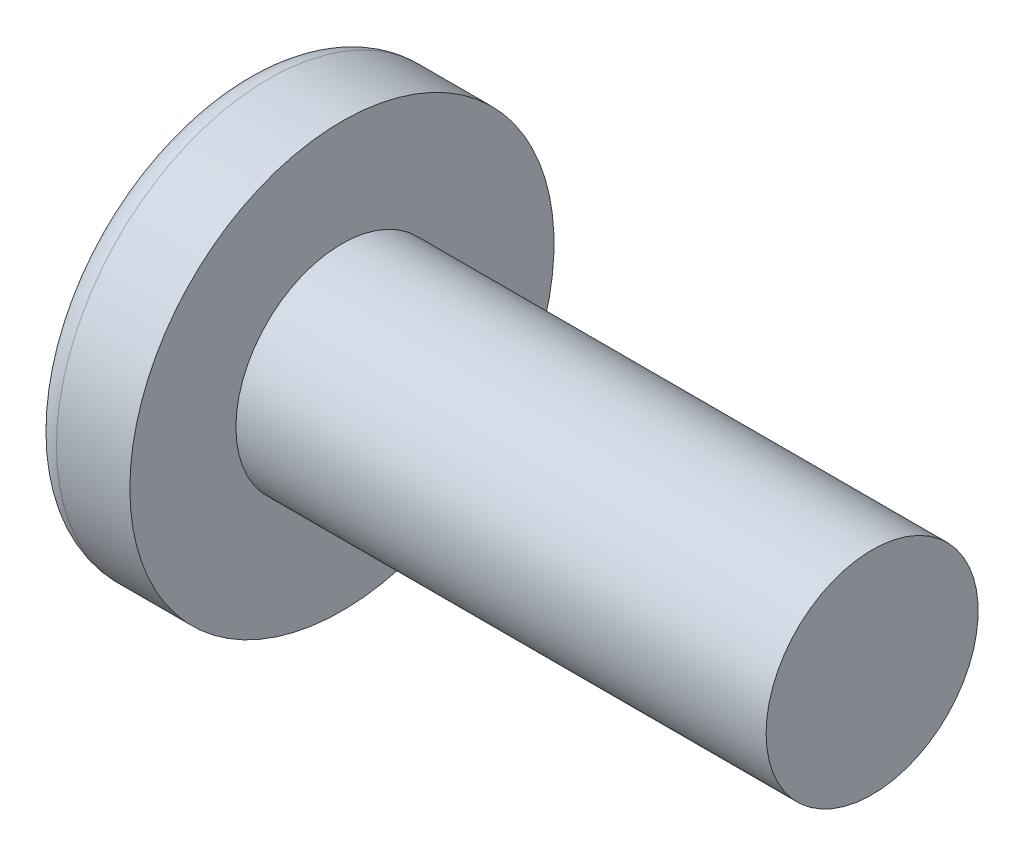
SolidWorks part; units mm, degrees
ref_plane "Plane1" through (0, 0, 0) normal (0, 0, 1) x (1, 0, 0)
ref_plane "Plane2" through (0, 0, 0) normal (0, 1, 0) x (1, 0, 0)
ref_plane "Plane3" through (0, 0, 0) normal (1, 0, 0) x (0, 0, -1)
sketch "BodySke" plane through (0, 0, 0) normal (0, 0, 1) x (1, 0, 0)
  line L0 (6, 4) -> (6, 8)
  line L1 (7.25, 6.35) -> (7.25, -3.175) construction
  line L2 (-25.4, 0) -> (127, 0) construction
  line L3 (26, 0) -> (0, 0)
  line L4 (6, 4) -> (26, 4)
  line L5 (26, 4) -> (26, 0)
  line L6 (3.2327, 8) -> (6, 8)
  line L7 (6, -4) -> (26, -4) construction
  line L8 (6, 6.35) -> (6, -3.175) construction
  arc A0 (2.4539, 7.6013) -> (0, 0) centre (13, 0) ccw
  arc A2 (2.4539, 7.6013) -> (3.2327, 8) centre (3.2327, 7.04) cw
  dimension "Head_crown_rad" = 13
  dimension "Head_fillet_rad" = 0.96
  dimension "Diameter" = 8
  dimension "Length" = 20
  dimension "Head_ht" = 6
  dimension "Head_dia" = 16
  dimension "Advance" = 1.25
  dimension "Thread_nom" = 20
revolve "Base-Revolve" add sketch "BodySke" angle 360 about L2
cosmetic thread "ThreadCosmetic" [suppressed] parameters "Thread_length"=18.75, "Thread_minor"=6.619
sketch "Sketch3" plane through (0, 0, 0) normal (1, 0, 0) x (0, 0, -1)
  line L0 (0.845, -4.51) -> (-0.845, -4.51)
  line L1 (0.845, -4.51) -> (0.845, 4.51)
  line L2 (-0.845, 4.51) -> (0.845, 4.51)
  line L3 (-0.845, 4.51) -> (-0.845, -4.51)
  dimension "Cross_dia" = 9.02
  dimension "D1" = 4.51
  dimension "Cross_width" = 1.69
  dimension "D2" = 0.845
ref_plane "Plane4" through (4.88, 0, 0) normal (1, 0, 0) x (0, 0, -1)
sketch "Sketch4" plane through (4.88, 0, 0) normal (1, 0, 0) x (0, 0, -1)
  line L0 (0.4225, -0.4225) -> (-0.4225, -0.4225)
  line L1 (0.4225, -0.4225) -> (0.4225, 0.4225)
  line L2 (-0.4225, 0.4225) -> (0.4225, 0.4225)
  line L3 (-0.4225, 0.4225) -> (-0.4225, -0.4225)
  dimension "D2" = 0.845
  dimension "D1" = 0.845
  dimension "D3" = 0.4225
  dimension "D4" = 0.4225
loft "Cut-Loft1" cut profiles "Sketch3", "Sketch4"
pattern_circular "CirPattern1" count 2 every 90 about axis through (0, 0, 0) along (1, 0, 0) of "Cut-Loft1"
sketch "ThdSchSke" plane through (0, 0, 0) normal (0, 0, 1) x (1, 0, 0)
  line L0 (7.25, -3.3095) -> (6.7665, -4)
  line L1 (7.25, -3.3095) -> (7.7335, -4)
  line L2 (7.7335, -4) -> (7.7335, -5)
  line L3 (-3.175, 0) -> (5.1513, 0) construction
  line L5 (7.7335, -5) -> (6.7665, -5)
  line L6 (6.7665, -5) -> (6.7665, -4)
  dimension "Diameter" = 8
  dimension "SideAngle" = 55
  dimension "VeeAngle" = 70
  dimension "Thread_minor" = 6.619
  dimension "Overcut" = 10
  dimension "Start" = 7.25
revolve "ThreadSchematic" [suppressed] cut sketch "ThdSchSke" angle 360 about L3
pattern_linear "ThdSchPat" [suppressed]
equation "\"D1@Sketch3\" = \"Cross_dia@Sketch3\" / 2"
equation "\"D2@Sketch3\" = \"Cross_width@Sketch3\" / 2"
equation "\"D1@Sketch4\" = \"Cross_width@Sketch3\" *.5"
equation "\"D2@Sketch4\" = \"D1@Sketch4\""
equation "\"D3@Sketch4\" = \"D1@Sketch4\" / 2"
equation "\"D4@Sketch4\" = \"D2@Sketch4\" / 2"
equation "\"Thread_length@ThreadCosmetic\" = ((sgn( (\"Length@BodySke\" - \"Advance@BodySke\" ) - \"Thread_nom@BodySke\" )-1)*( (\"Length@BodySke\" - \"Advance@BodySke\" ) - \"Thread_nom@BodySke\" ))/-2+ \"Thread_nom@BodySke\""
equation "\"Thread_minor@ThdSchSke\" = \"Thread_minor@ThreadCosmetic\""
equation "\"Diameter@ThdSchSke\" = \"Diameter@BodySke\""
equation "\"Overcut@ThdSchSke\" = \"Diameter@BodySke\" * 1.25"
equation "\"Start@ThdSchSke\" = \"Head_ht@BodySke\" + \"Length@BodySke\" - \"Thread_length@ThreadCosmetic\"  '---Non-countersunk---"
equation "\"Num_threads@ThdSchPat\" = int( \"Thread_length@ThreadCosmetic\" / \"Advance@BodySke\" + 0.999 )  + 1"
equation "\"Advance@ThdSchPat\" = \"Thread_length@ThreadCosmetic\" /  (\"Num_threads@ThdSchPat\" - 1) 'relax it"
